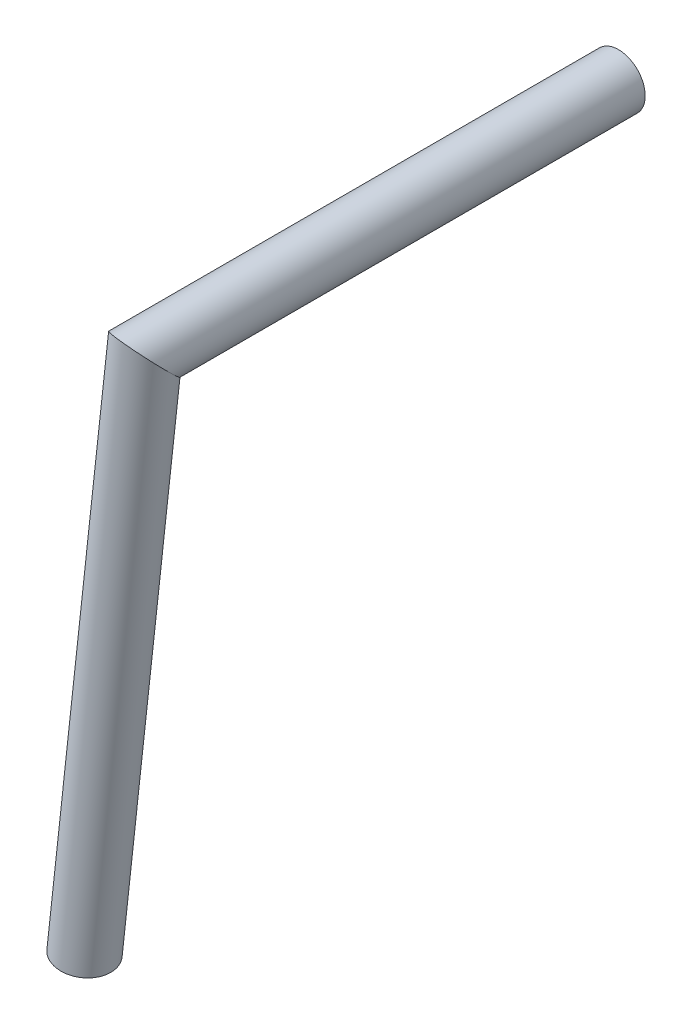
SolidWorks part; units mm, degrees
ref_plane "Front Plane" through (0, 0, 0) normal (0, 0, 1) x (1, 0, 0)
ref_plane "Top Plane" through (0, 0, 0) normal (0, 1, 0) x (1, 0, 0)
ref_plane "Right Plane" through (0, 0, 0) normal (1, 0, 0) x (0, 0, -1)
sketch "Sketch1" plane through (0, 0, 0) normal (0, 0, 1) x (1, 0, 0)
  circle A0 centre (0, 0) radius 2.9836
sketch3d "3DSketch3"
  line L0 (0, 0, 0) -> (0, 0, 52.9245)
  line L1 (0, 0, 52.9245) -> (-7.494, -62.0613, 52.1047)
  point P3 (-7.494, -62.0613, 52.1047)
sweep "Sweep3" add profiles "Sketch1" path "3DSketch3"
